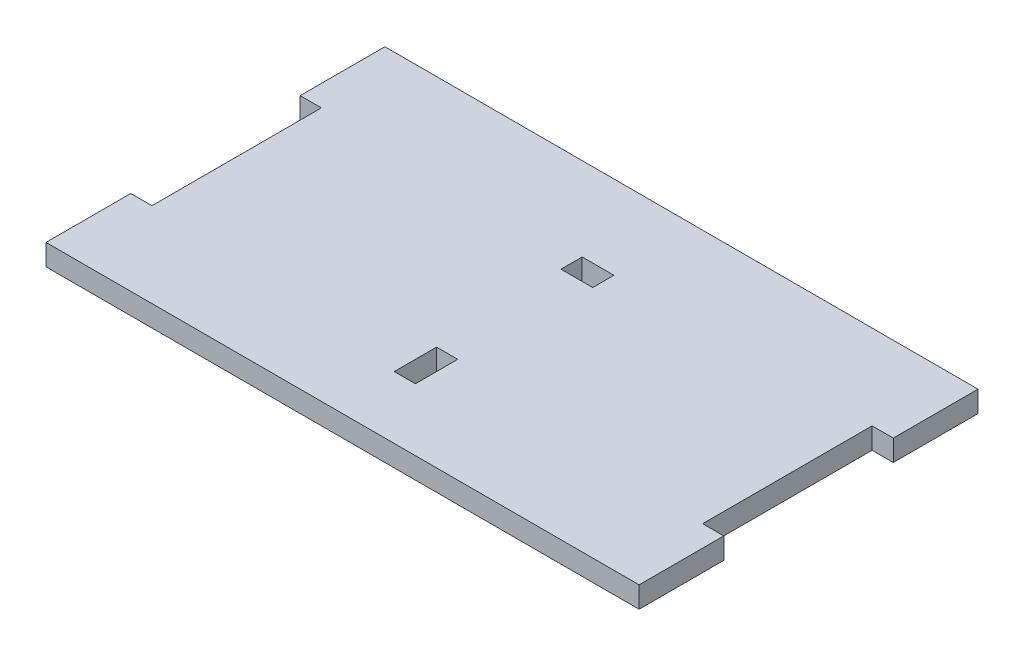
SolidWorks part; units mm, degrees
material "Balsa"
ref_plane "Front Plane" through (0, 0, 0) normal (0, 0, 1) x (1, 0, 0)
ref_plane "Top Plane" through (0, 0, 0) normal (0, 1, 0) x (1, 0, 0)
ref_plane "Right Plane" through (0, 0, 0) normal (1, 0, 0) x (0, 0, -1)
sketch "Sketch1" plane through (0, 0, 0) normal (0, 1, 0) x (1, 0, 0)
  line L0 (-41.275, -12.7) -> (-41.275, 12.7)
  line L1 (-41.275, -25.4) -> (41.275, -25.4)
  line L2 (-41.275, 25.4) -> (41.275, 25.4)
  line L3 (41.275, -12.7) -> (41.275, 12.7)
  line L4 (-41.275, 0) -> (41.275, 0) construction
  line L5 (0, 25.4) -> (0, -25.4) construction
  line L6 (41.275, 25.4) -> (44.45, 25.4)
  line L7 (44.45, 25.4) -> (44.45, 12.7)
  line L8 (44.45, 12.7) -> (41.275, 12.7)
  line L9 (-2.3813, 9.7155) -> (-2.3813, 0) construction
  line L10 (1.5875, -9.7155) -> (1.5875, 0) construction
  line L11 (44.45, -12.7) -> (41.275, -12.7)
  line L12 (44.45, -25.4) -> (44.45, -12.7)
  line L13 (41.275, -25.4) -> (44.45, -25.4)
  line L14 (-41.275, 25.4) -> (-44.45, 25.4)
  line L15 (-44.45, 25.4) -> (-44.45, 12.7)
  line L16 (-44.45, 12.7) -> (-41.275, 12.7)
  line L17 (-44.45, -12.7) -> (-41.275, -12.7)
  line L18 (-41.275, -25.4) -> (-44.45, -25.4)
  line L19 (-44.45, -25.4) -> (-44.45, -12.7)
  line L21 (-2.3813, 9.7155) -> (2.3812, 9.7155)
  line L22 (-2.3813, 9.7155) -> (-2.3813, 12.8905)
  line L23 (-2.3813, 12.8905) -> (2.3812, 12.8905)
  line L24 (2.3812, 9.7155) -> (2.3812, 12.8905)
  line L26 (-1.5875, -9.7155) -> (1.5875, -9.7155)
  line L27 (-1.5875, -9.7155) -> (-1.5875, -16.0655)
  line L28 (-1.5875, -16.0655) -> (1.5875, -16.0655)
  line L29 (1.5875, -9.7155) -> (1.5875, -16.0655)
  point P1 (0, 0)
  point P11 (0, 0)
  point P14 (44.45, 25.4)
  point P29 (0, -9.7155)
  point P30 (0, 9.7155)
  point P37 (0, 0)
  point P39 (0, -25.4)
  point P40 (-44.45, -25.4)
  point P41 (-41.275, -25.4)
  point P42 (-41.275, -12.7)
  point P43 (41.275, 0)
  point P44 (0, 0)
  dimension "D1" = 25.4
  dimension "D2" = 12.7
  dimension "D3" = 3.175
  dimension "D4" = 88.9
  dimension "D5" = 28.956
  dimension "D6" = 6.35
  dimension "D7" = 3.175
  dimension "D8" = 4.7625
  dimension "D9" = 3.175
extrude "Boss-Extrude1" add sketch "Sketch1" along normal blind 3.175
